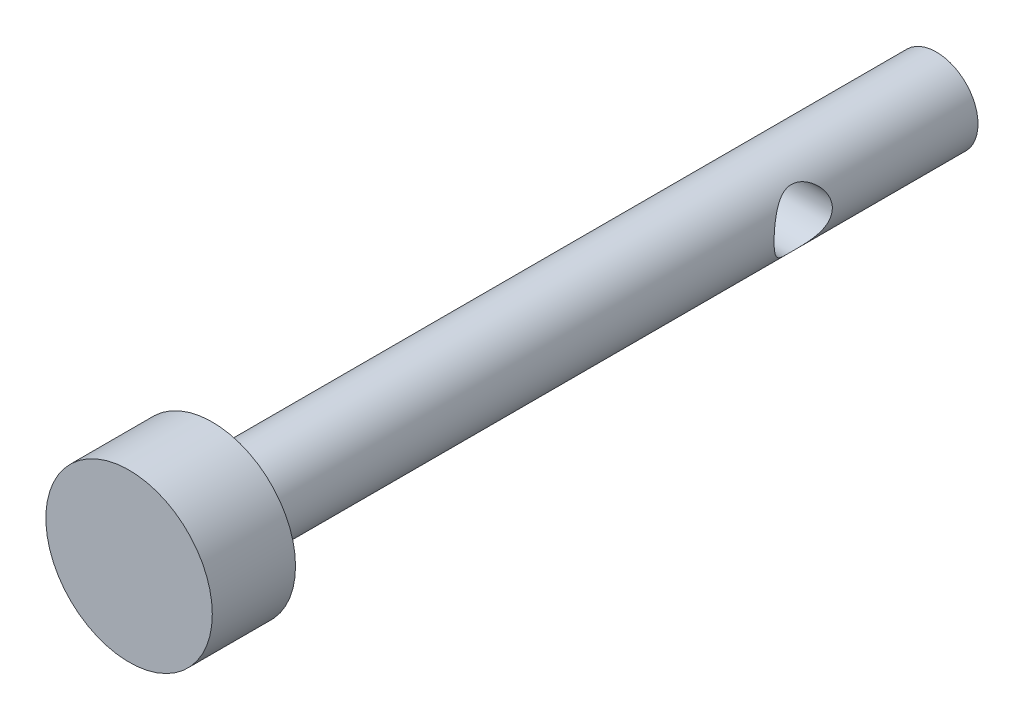
SolidWorks part; units mm, degrees
ref_plane "Front Plane" through (0, 0, 0) normal (0, 0, 1) x (1, 0, 0)
ref_plane "Top Plane" through (0, 0, 0) normal (0, 1, 0) x (1, 0, 0)
ref_plane "Right Plane" through (0, 0, 0) normal (1, 0, 0) x (0, 0, -1)
sketch "Sketch1" plane through (0, 0, 0) normal (0, 0, 1) x (1, 0, 0)
  circle A0 centre (0, 0) radius 2.5
  dimension "D1" = 5
extrude "Boss-Extrude1" add sketch "Sketch1" along normal blind 43.5
sketch "Sketch2" plane through (0, 0, 43.5) normal (0, 0, 1) x (1, 0, 0)
  circle A0 centre (0, 0) radius 5
  dimension "D1" = 10
extrude "Boss-Extrude2" add sketch "Sketch2" along normal blind 5
sketch "Sketch3" plane through (0, 0, 0) normal (1, 0, 0) x (0, 0, -1)
  line L0 (-43.5, -5) -> (-43.5, 5) construction
  circle A0 centre (-10.5, 0) radius 1.75
  dimension "D2" = 3.5
  dimension "D1" = 33
extrude "Cut-Extrude2" cut sketch "Sketch3" against normal blind 20 from offset 10
